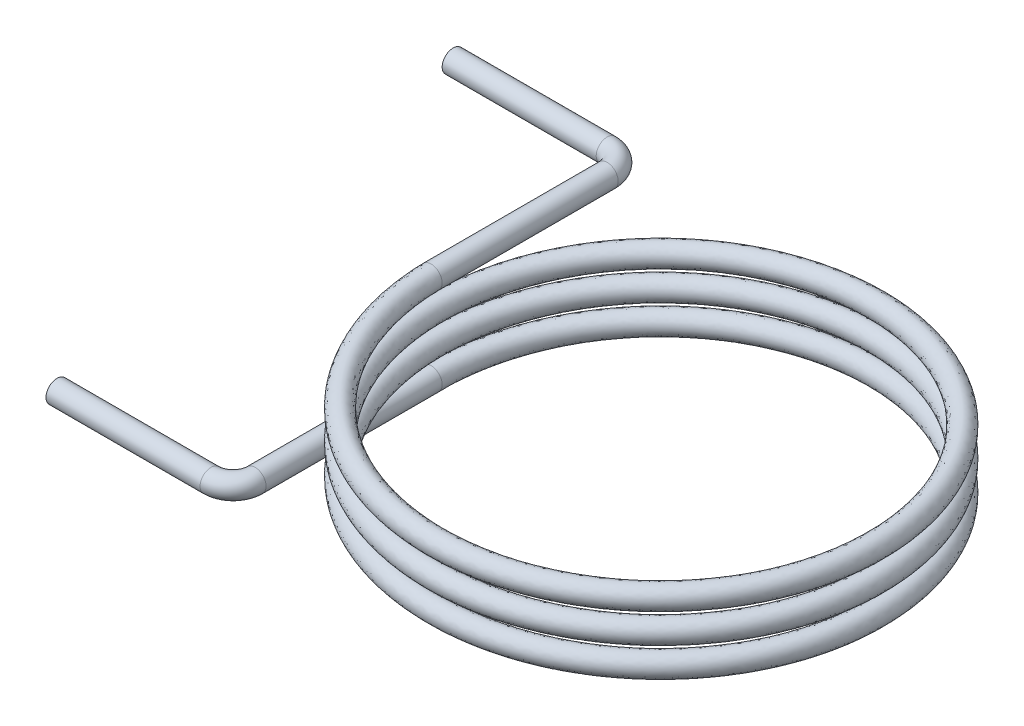
SolidWorks part; units mm, degrees
material "Nichel"
ref_plane "Piano frontale" through (0, 0, 0) normal (0, 0, 1) x (1, 0, 0)
ref_plane "Piano superiore" through (0, 0, 0) normal (0, 1, 0) x (1, 0, 0)
ref_plane "Piano destro" through (0, 0, 0) normal (1, 0, 0) x (0, 0, -1)
sketch "Schizzo1" plane through (0, 0, 0) normal (0, 1, 0) x (1, 0, 0)
  circle A0 centre (0, 0) radius 5
  dimension "D1" = 10
curve "Elica/Spirale1" pitch 0.6667 height 2 turns 3
sketch "Schizzo4" plane through (0, 0, 0) normal (0, 0, 1) x (1, 0, 0)
  circle A0 centre (-5, 0) radius 0.25
  spline S0 degree 3 poles (-5, 0) (-5, 0.0138) (-4.7397, 0.0417) (-3.6276, 0.0833) (-1.4084, 0.1389) (1.4084, 0.1944) (3.6276, 0.25) (4.7397, 0.2917) (5.1302, 0.3333) (4.7397, 0.375) (3.6276, 0.4167) (1.4084, 0.4722) (-1.4084, 0.5278) (-3.6276, 0.5833) (-4.7397, 0.625) (-5.1302, 0.6667) (-4.7397, 0.7083) (-3.6276, 0.75) (-1.4084, 0.8056) (1.4084, 0.8611) (3.6276, 0.9167) (4.7397, 0.9583) (5.1302, 1) (4.7397, 1.0417) (3.6276, 1.0833) (1.4084, 1.1389) (-1.4084, 1.1944) (-3.6276, 1.25) (-4.7397, 1.2917) (-5.1302, 1.3333) (-4.7397, 1.375) (-3.6276, 1.4167) (-1.4084, 1.4722) (1.4084, 1.5278) (3.6276, 1.5833) (4.7397, 1.625) (5.1302, 1.6667) (4.7397, 1.7083) (3.6276, 1.75) (1.4084, 1.8056) (-1.4084, 1.8611) (-3.6276, 1.9167) (-4.7397, 1.9583) (-5, 1.9862) (-5, 2) knots 0 0 0 0 0.020833 0.041667 0.0625 0.104167 0.125 0.145833 0.166667 0.1875 0.208333 0.229167 0.270833 0.291667 0.3125 0.333333 0.354167 0.375 0.395833 0.4375 0.458333 0.479167 0.5 0.520833 0.541667 0.5625 0.604167 0.625 0.645833 0.666667 0.6875 0.708333 0.729167 0.770833 0.791667 0.8125 0.833333 0.854167 0.875 0.895833 0.9375 0.958333 0.979167 1 1 1 1 construction
  dimension "D1" = 0.5
sweep "Sweep2" add profiles "Schizzo4" path "Elica/Spirale1"
ref_plane "Piano1" through (-5, 0, 0) normal (1, 0, 0) x (0, 0, -1)
sketch3d "Schizzo3D3"
  line L0 (-5, 2, 0) -> (-5, 2, -4)
  line L1 (-5.5, 2, -4.5) -> (-9, 2, -4.5)
  arc A0 (-5, 2, -4) -> (-5.5, 2, -4.5) centre (-5.5, 2, -4) ccw
  spline S0 degree 3 poles (-5, 0, 0) (-5, 0.0138, -0.6503) (-4.7397, 0.0417, -1.9651) (-3.6276, 0.0833, -3.6271) (-1.9632, 0.125, -4.7398) (0, 0.1667, -5.1301) (1.9632, 0.2083, -4.7397) (3.6276, 0.25, -3.6276) (4.7397, 0.2917, -1.9632) (5.1302, 0.3333, 0) (4.7397, 0.375, 1.9632) (3.6276, 0.4167, 3.6276) (1.9632, 0.4583, 4.7397) (0, 0.5, 5.1302) (-1.9632, 0.5417, 4.7397) (-3.6276, 0.5833, 3.6276) (-4.7397, 0.625, 1.9632) (-5.1302, 0.6667, 0) (-4.7397, 0.7083, -1.9632) (-3.6276, 0.75, -3.6276) (-1.9632, 0.7917, -4.7397) (0, 0.8333, -5.1302) (1.9632, 0.875, -4.7397) (3.6276, 0.9167, -3.6276) (4.7397, 0.9583, -1.9632) (5.1302, 1, 0) (4.7397, 1.0417, 1.9632) (3.6276, 1.0833, 3.6276) (1.9632, 1.125, 4.7397) (0, 1.1667, 5.1302) (-1.9632, 1.2083, 4.7397) (-3.6276, 1.25, 3.6276) (-4.7397, 1.2917, 1.9632) (-5.1302, 1.3333, 0) (-4.7397, 1.375, -1.9632) (-3.6276, 1.4167, -3.6276) (-1.9632, 1.4583, -4.7397) (0, 1.5, -5.1302) (1.9632, 1.5417, -4.7397) (3.6276, 1.5833, -3.6276) (4.7397, 1.625, -1.9632) (5.1302, 1.6667, 0) (4.7397, 1.7083, 1.9632) (3.6276, 1.75, 3.6276) (1.9632, 1.7917, 4.7397) (0, 1.8333, 5.1301) (-1.9632, 1.875, 4.7398) (-3.6276, 1.9167, 3.6271) (-4.7397, 1.9583, 1.9651) (-5, 1.9862, 0.6503) (-5, 2, 0) knots 0 0 0 0 0.020833 0.041667 0.0625 0.083333 0.104167 0.125 0.145833 0.166667 0.1875 0.208333 0.229167 0.25 0.270833 0.291667 0.3125 0.333333 0.354167 0.375 0.395833 0.416667 0.4375 0.458333 0.479167 0.5 0.520833 0.541667 0.5625 0.583333 0.604167 0.625 0.645833 0.666667 0.6875 0.708333 0.729167 0.75 0.770833 0.791667 0.8125 0.833333 0.854167 0.875 0.895833 0.916667 0.9375 0.958333 0.979167 1 1 1 1 construction
  point P9 (-5, 2, -4.5)
  point P10 (-5.5, 2.5, -4)
  dimension "D1" = 0.5
  dimension "D2" = 4.5
  dimension "D3" = 4
sweep "Sweep3" add path "Schizzo3D3" circular profile diameter 0.5 parameters "D3"=0.5
sketch3d "Schizzo3D4"
  line L0 (-5, 0, 0) -> (-5, 0, 4)
  line L1 (-5.5, 0, 4.5) -> (-9, 0, 4.5)
  arc A0 (-5, 0, 4) -> (-5.5, 0, 4.5) centre (-5.5, 0, 4) ccw
  spline S0 degree 3 poles (-5, 0, 0) (-5, 0.0138, -0.6503) (-4.7397, 0.0417, -1.9651) (-3.6276, 0.0833, -3.6271) (-1.9632, 0.125, -4.7398) (0, 0.1667, -5.1301) (1.9632, 0.2083, -4.7397) (3.6276, 0.25, -3.6276) (4.7397, 0.2917, -1.9632) (5.1302, 0.3333, 0) (4.7397, 0.375, 1.9632) (3.6276, 0.4167, 3.6276) (1.9632, 0.4583, 4.7397) (0, 0.5, 5.1302) (-1.9632, 0.5417, 4.7397) (-3.6276, 0.5833, 3.6276) (-4.7397, 0.625, 1.9632) (-5.1302, 0.6667, 0) (-4.7397, 0.7083, -1.9632) (-3.6276, 0.75, -3.6276) (-1.9632, 0.7917, -4.7397) (0, 0.8333, -5.1302) (1.9632, 0.875, -4.7397) (3.6276, 0.9167, -3.6276) (4.7397, 0.9583, -1.9632) (5.1302, 1, 0) (4.7397, 1.0417, 1.9632) (3.6276, 1.0833, 3.6276) (1.9632, 1.125, 4.7397) (0, 1.1667, 5.1302) (-1.9632, 1.2083, 4.7397) (-3.6276, 1.25, 3.6276) (-4.7397, 1.2917, 1.9632) (-5.1302, 1.3333, 0) (-4.7397, 1.375, -1.9632) (-3.6276, 1.4167, -3.6276) (-1.9632, 1.4583, -4.7397) (0, 1.5, -5.1302) (1.9632, 1.5417, -4.7397) (3.6276, 1.5833, -3.6276) (4.7397, 1.625, -1.9632) (5.1302, 1.6667, 0) (4.7397, 1.7083, 1.9632) (3.6276, 1.75, 3.6276) (1.9632, 1.7917, 4.7397) (0, 1.8333, 5.1301) (-1.9632, 1.875, 4.7398) (-3.6276, 1.9167, 3.6271) (-4.7397, 1.9583, 1.9651) (-5, 1.9862, 0.6503) (-5, 2, 0) knots 0 0 0 0 0.020833 0.041667 0.0625 0.083333 0.104167 0.125 0.145833 0.166667 0.1875 0.208333 0.229167 0.25 0.270833 0.291667 0.3125 0.333333 0.354167 0.375 0.395833 0.416667 0.4375 0.458333 0.479167 0.5 0.520833 0.541667 0.5625 0.583333 0.604167 0.625 0.645833 0.666667 0.6875 0.708333 0.729167 0.75 0.770833 0.791667 0.8125 0.833333 0.854167 0.875 0.895833 0.916667 0.9375 0.958333 0.979167 1 1 1 1 construction
  point P14 (-5, 0, 4.5)
  point P15 (-5.5, -0.5, 4)
  dimension "D3" = 0.5
  dimension "D1" = 4.5
  dimension "D2" = 4
sweep "Sweep4" add path "Schizzo3D4" circular profile diameter 0.5 parameters "D3"=0.5
sketch "Schizzo5" plane through (0, 0, 0) normal (0, 0, 1) x (1, 0, 0)
  line L0 (0, 0) -> (0, 6.7975) construction
